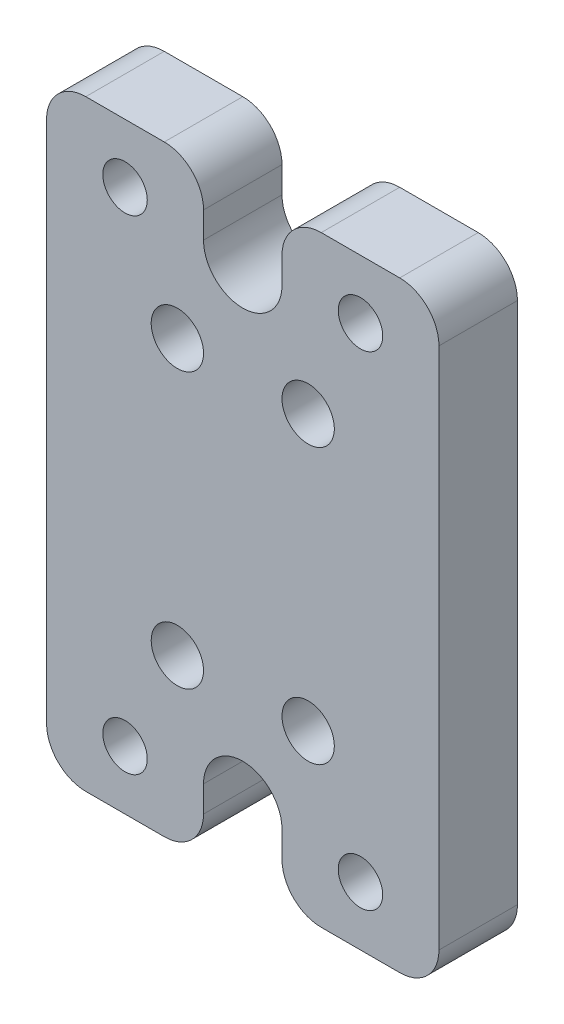
SolidWorks part; units mm, degrees
ref_plane "Front Plane" through (0, 0, 0) normal (0, 0, 1) x (1, 0, 0)
ref_plane "Top Plane" through (0, 0, 0) normal (0, 1, 0) x (1, 0, 0)
ref_plane "Right Plane" through (0, 0, 0) normal (1, 0, 0) x (0, 0, -1)
sketch "Sketch1" plane through (0, 0, 0) normal (0, 0, 1) x (1, 0, 0)
  line L0 (-1000, 0) -> (49000, 0) construction
  line L1 (-12, 23) -> (-6, 23)
  line L2 (-15, 20) -> (-15, -20)
  line L3 (-12, -23) -> (-6, -23)
  line L4 (15, 20) -> (15, -20)
  line L5 (0, -1000) -> (0, 49000) construction
  line L8 (-3, 20) -> (-3, 18)
  line L10 (3, 20) -> (3, 18)
  line L11 (3, -20) -> (3, -18)
  line L13 (-3, -20) -> (-3, -18)
  line L14 (6, 23) -> (12, 23)
  line L15 (6, -23) -> (12, -23)
  circle A0 centre (-9, 18.5) radius 1.7
  circle A2 centre (9, 18.5) radius 1.7
  circle A3 centre (9, -18.5) radius 1.7
  circle A4 centre (-9, -18.5) radius 1.7
  arc A5 (12, -23) -> (15, -20) centre (12, -20) ccw
  arc A6 (6, -23) -> (3, -20) centre (6, -20) cw
  arc A7 (-3, -20) -> (-6, -23) centre (-6, -20) cw
  arc A8 (-12, -23) -> (-15, -20) centre (-12, -20) cw
  arc A9 (15, 20) -> (12, 23) centre (12, 20) ccw
  arc A10 (6, 23) -> (3, 20) centre (6, 20) ccw
  arc A11 (-3, 20) -> (-6, 23) centre (-6, 20) ccw
  arc A12 (-15, 20) -> (-12, 23) centre (-12, 20) cw
  arc A13 (-3, 18) -> (3, 18) centre (0, 18) ccw
  arc A14 (3, -18) -> (-3, -18) centre (0, -18) ccw
  circle A15 centre (-5, 10.5) radius 2
  circle A16 centre (5, 10.5) radius 2
  circle A17 centre (5, -10.5) radius 2
  circle A18 centre (-5, -10.5) radius 2
  point P29 (3, -23)
  point P32 (-3, -23)
  point P39 (3, 23)
  point P42 (-3, 23)
  point P55 (0, 0)
  dimension "D3" = 3.4
  dimension "D7" = 3
  dimension "D9" = 3
  dimension "D10" = 3
  dimension "D11" = 4
  dimension "D1" = 18
  dimension "D2" = 37
  dimension "D4" = 6
  dimension "D5" = 4.5
  dimension "D6" = 6
  dimension "D8" = 5
  dimension "D12" = 21
  dimension "D13" = 10
extrude "Boss-Extrude1" add sketch "Sketch1" along normal blind 6
